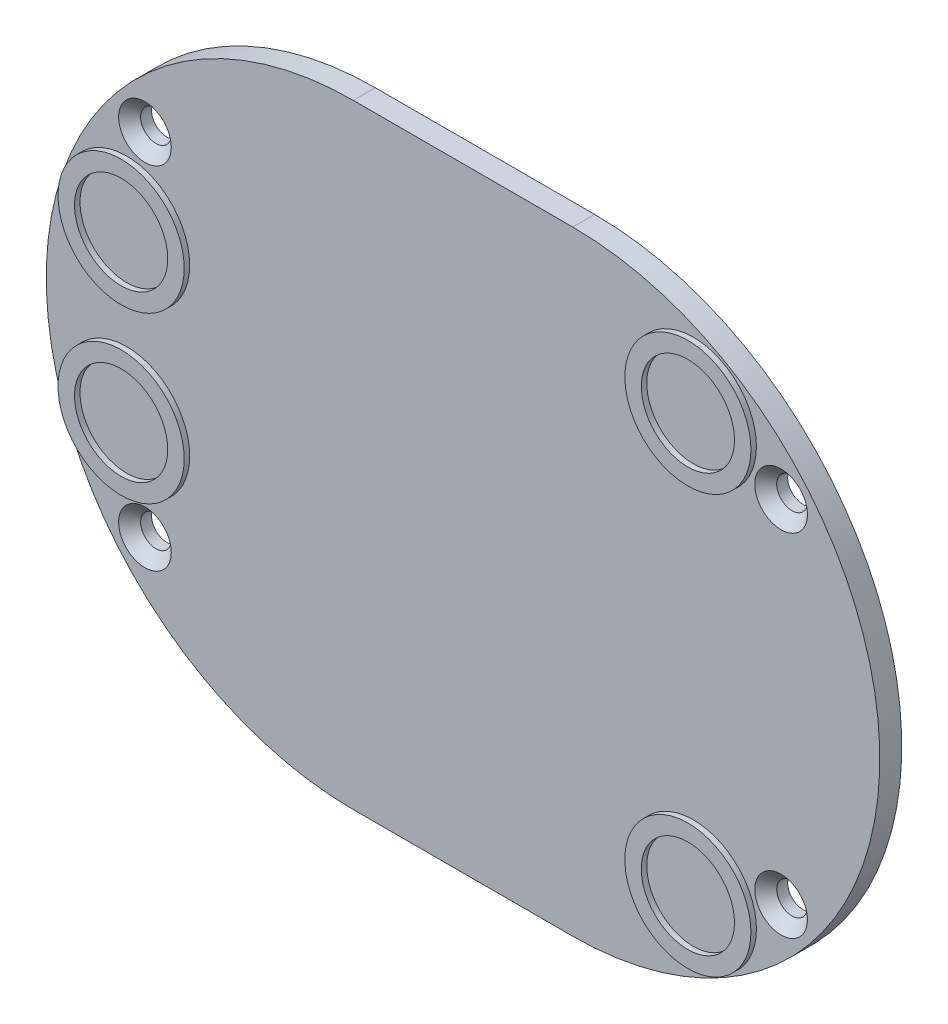
SolidWorks part; units mm, degrees
ref_plane "前视基准面" through (0, 0, 0) normal (0, 0, 1) x (1, 0, 0)
ref_plane "上视基准面" through (0, 0, 0) normal (0, 1, 0) x (1, 0, 0)
ref_plane "右视基准面" through (0, 0, 0) normal (1, 0, 0) x (0, 0, -1)
sketch "草图3" plane through (0, 0, 0) normal (0, 0, 1) x (1, 0, 0)
  line L0 (10, -28) -> (-10, -28) construction
  line L1 (-10, 28) -> (10, 28) construction
  line L2 (10, -28) -> (-10, -28)
  line L3 (-10, 28) -> (10, 28)
  arc A0 (-10, 28) -> (-10, -28) centre (-10, 0) ccw construction
  arc A1 (10, -28) -> (10, 28) centre (10, 0) ccw construction
  arc A2 (-10, 28) -> (-10, -28) centre (-10, 0) ccw
  arc A3 (10, -28) -> (10, 28) centre (10, 0) ccw
extrude "凸台-拉伸2" add sketch "草图3" along normal blind 2 contours L3 A3 L2 A2
hole_wizard "打孔尺寸(%根据十字)槽沉头自攻螺钉的类型0" positions "草图5" profile "草图6" countersink size "ST2.2" standard "GB"
sketch "草图5" plane through (0, 0, 2) normal (0, 0, 1) x (1, 0, 0)
  line L1 (12.1906, 0) -> (-13.0853, 0) construction
  line L2 (14.2037, 0) -> (-13.0853, 0) construction
  line L5 (-29, 16) -> (29, 16)
  line L6 (-29, 16) -> (-29, -16)
  line L7 (-29, -16) -> (29, -16)
  line L8 (29, 16) -> (29, -16)
  line L9 (0, -7.6396) -> (0, 21.327) construction
  point P0 (-29, 16)
  point P2 (-29, -16)
  point P4 (29, 16)
  point P6 (29, -16)
  dimension "D1" = 32
  dimension "D2" = 58
sketch "草图6" plane through (-29, 16, 2) normal (1, 0, 0) x (0, -1, 0)
  line L0 (0, 0) -> (0, 10.9412)
  line L1 (0, 10.9412) -> (1.4, 10.1)
  line L2 (1.4, 10.1) -> (1.4, 1)
  line L3 (1.4, 1) -> (2.4, 0)
  line L5 (2.4, 0) -> (0, 0)
  line L6 (-1.4, 1) -> (-2.4, 0) construction
  line L10 (0, 10.9412) -> (-1.4, 10.1) construction
  line L11 (0, -6.35) -> (0, 107.95) construction
  dimension "孔直径" = 2.8
  dimension "孔深度" = 10.1
  dimension "近端锥形沉头孔直径" = 4.8
  dimension "近端锥形沉头孔角度" = 90
  dimension "导头角度" = 118
sketch "草图7" plane through (0, 0, 2) normal (0, 0, 1) x (1, 0, 0)
  circle A0 centre (-30.6732, 7.5244) radius 4.25
  circle A1 centre (-30.6732, -7.5244) radius 4.25
  circle A2 centre (21, -19.0526) radius 4.25
  circle A3 centre (21, 19.0526) radius 4.25
  dimension "D1" = 8.5
extrude "拉伸-薄壁1" add sketch "草图7" along normal blind 0.5 thin
